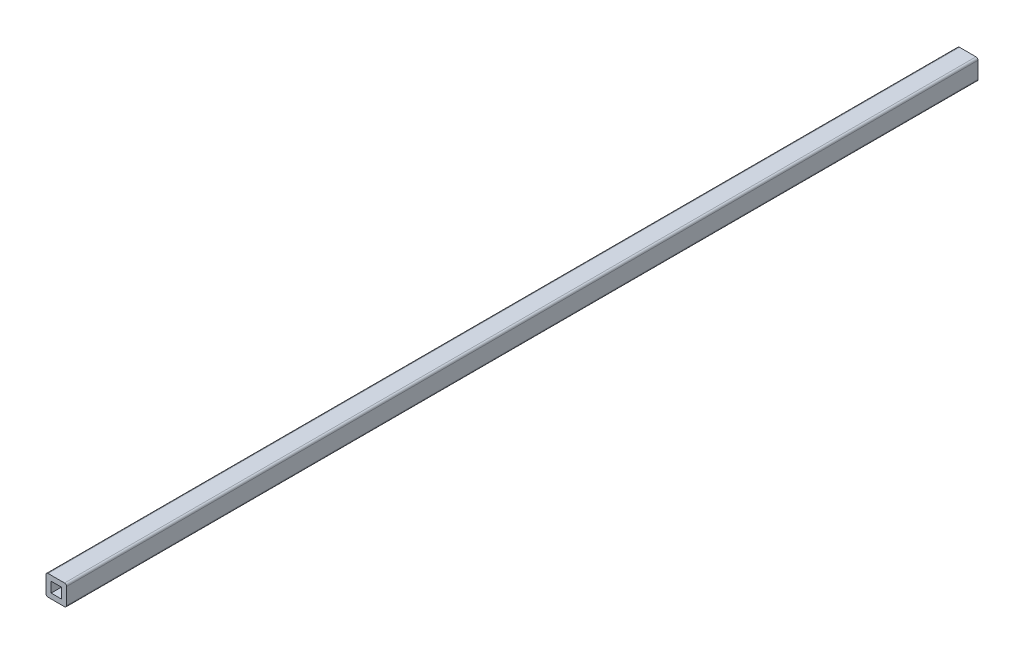
SolidWorks part; units mm, degrees
ref_plane "Front Plane" through (0, 0, 0) normal (0, 0, 1) x (1, 0, 0)
ref_plane "Top Plane" through (0, 0, 0) normal (0, 1, 0) x (1, 0, 0)
ref_plane "Right Plane" through (0, 0, 0) normal (1, 0, 0) x (0, 0, -1)
sketch "Sketch1" plane through (0, 0, 0) normal (0, 0, 1) x (1, 0, 0)
  line L1 (-25.4, 25.4) -> (25.4, 25.4)
  line L2 (-25.4, 25.4) -> (-25.4, -25.4)
  line L3 (-25.4, -25.4) -> (25.4, -25.4)
  line L4 (25.4, 25.4) -> (25.4, -25.4)
  line L5 (-25.4, 25.4) -> (25.4, -25.4) construction
  line L6 (-25.4, -25.4) -> (25.4, 25.4) construction
  line L7 (12.7, -12.7) -> (-12.7, -12.7)
  line L8 (12.7, -12.7) -> (12.7, 12.7)
  line L9 (12.7, 12.7) -> (-12.7, 12.7)
  line L10 (-12.7, -12.7) -> (-12.7, 12.7)
  line L11 (12.7, -12.7) -> (-12.7, 12.7) construction
  line L12 (12.7, 12.7) -> (-12.7, -12.7) construction
  point P0 (0, 0)
  point P5 (0, 0)
  dimension "D1" = 50.8
  dimension "D2" = 50.8
  dimension "D3" = 38.1
extrude "Boss-Extrude1" add sketch "Sketch1" along normal blind 2250.44
fillet "Fillet1" radius 5 4 edges at (25.4, -25.4, 1125.22) (-25.4, -25.4, 1125.22) (-25.4, 25.4, 1125.22) (25.4, 25.4, 1125.22)
